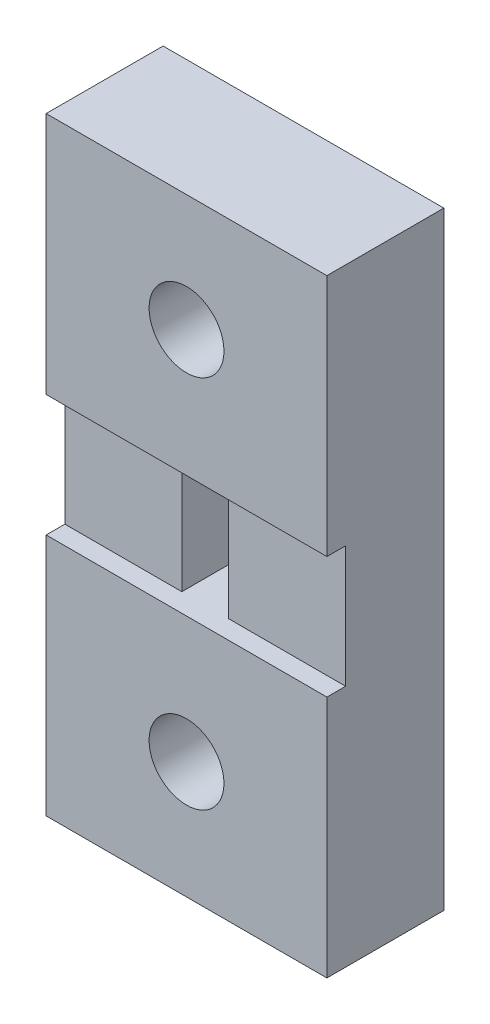
SolidWorks part; units mm, degrees
ref_plane "Front Plane" through (0, 0, 0) normal (0, 0, 1) x (1, 0, 0)
ref_plane "Top Plane" through (0, 0, 0) normal (0, 1, 0) x (1, 0, 0)
ref_plane "Right Plane" through (0, 0, 0) normal (1, 0, 0) x (0, 0, -1)
sketch "Sketch1" plane through (0, 0, 0) normal (0, 0, 1) x (1, 0, 0)
  line L0 (0, -8) -> (0, 8)
  line L1 (6, -13) -> (-6, -13)
  line L2 (6, -13) -> (6, 13)
  line L3 (6, 13) -> (-6, 13)
  line L4 (-6, -13) -> (-6, 13)
  line L5 (6, -13) -> (-6, 13) construction
  line L6 (6, 13) -> (-6, -13) construction
  line L8 (-1, -2.6) -> (1, -2.6)
  line L9 (-1, -2.6) -> (-1, 2.6)
  line L10 (-1, 2.6) -> (1, 2.6)
  line L11 (1, -2.6) -> (1, 2.6)
  line L12 (-1, -2.6) -> (1, 2.6) construction
  line L13 (-1, 2.6) -> (1, -2.6) construction
  circle A0 centre (0, 8) radius 1.6
  circle A1 centre (0, -8) radius 1.6
  point P0 (0, 0)
  point P9 (0, 0)
  point P11 (0, 0)
  dimension "D4" = 3.2
  dimension "D5" = 3.2
  dimension "D1" = 26
  dimension "D2" = 12
  dimension "D3" = 16
  dimension "D6" = 5.2
  dimension "D7" = 2
extrude "Boss-Extrude1" add sketch "Sketch1" along normal blind 5
sketch "Sketch3" plane through (0, 0, 5) normal (0, 0, 1) x (1, 0, 0)
  line L0 (6, -13) -> (6, 13) construction
  line L1 (-6, -2.6) -> (6, -2.6)
  line L2 (-6, -2.6) -> (-6, 2.6)
  line L3 (-6, 2.6) -> (6, 2.6)
  line L4 (6, -2.6) -> (6, 2.6)
  line L5 (-6, -2.6) -> (6, 2.6) construction
  line L6 (-6, 2.6) -> (6, -2.6) construction
  line L7 (-1, 2.6) -> (1, 2.6) construction
  point P0 (0, 0)
extrude "Cut-Extrude1" cut sketch "Sketch3" against normal blind 0.8
sketch "Sketch4" plane through (0, 0, 0) normal (0, 0, -1) x (-1, 0, 0)
  line L0 (-6, -13) -> (6, -13) construction
  line L1 (1.7321, 11) -> (-1.7321, 11)
  line L2 (-1.7321, 11) -> (-3.4641, 8)
  line L3 (-3.4641, 8) -> (-1.7321, 5)
  line L4 (-1.7321, 5) -> (1.7321, 5)
  line L5 (1.7321, 5) -> (3.4641, 8)
  line L6 (3.4641, 8) -> (1.7321, 11)
  line L7 (1.7321, -5) -> (-1.7321, -5)
  line L8 (-1.7321, -5) -> (-3.4641, -8)
  line L9 (-3.4641, -8) -> (-1.7321, -11)
  line L10 (-1.7321, -11) -> (1.7321, -11)
  line L11 (1.7321, -11) -> (3.4641, -8)
  line L12 (3.4641, -8) -> (1.7321, -5)
  circle A0 centre (0, 8) radius 3 construction
  circle A1 centre (0, -8) radius 3 construction
  dimension "D2" = 6
  dimension "D1" = 6
extrude "Cut-Extrude2" cut sketch "Sketch4" against normal blind 2.5
